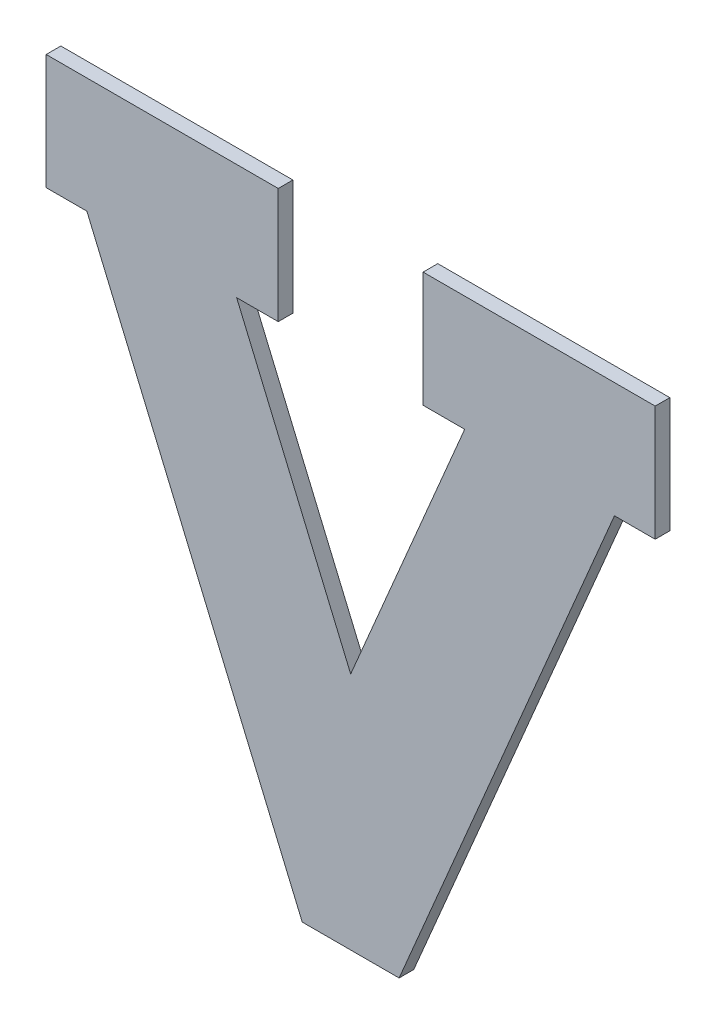
SolidWorks part; units mm, degrees
material "Copper"
ref_plane "Front Plane" through (0, 0, 0) normal (0, 0, 1) x (1, 0, 0)
ref_plane "Top Plane" through (0, 0, 0) normal (0, 1, 0) x (1, 0, 0)
ref_plane "Right Plane" through (0, 0, 0) normal (1, 0, 0) x (0, 0, -1)
sketch "Sketch1" plane through (0, 0, 0) normal (0, 0, 1) x (1, 0, 0)
  line B0 (326.5754, 440.106) -> (356.1251, 440.106)
  line B1 (356.1251, 440.106) -> (276.5171, 252.3248)
  line B2 (276.5171, 252.3248) -> (196.9092, 440.106)
  line B3 (196.9092, 440.106) -> (226.4589, 440.106)
  line B4 (226.4589, 440.106) -> (226.4589, 565.4544)
  line B5 (226.4589, 565.4544) -> (0, 565.4544)
  line B6 (0, 565.4544) -> (0, 440.106)
  line B7 (0, 440.106) -> (39.5592, 440.106)
  line B8 (39.5592, 440.106) -> (226.1378, 0)
  line B9 (226.1378, 0) -> (326.8965, 0)
  line B10 (326.8965, 0) -> (513.4751, 440.106)
  line B11 (513.4751, 440.106) -> (553.0343, 440.106)
  line B12 (553.0343, 440.106) -> (553.0343, 565.4544)
  line B13 (553.0343, 565.4544) -> (326.5754, 565.4544)
  line B14 (326.5754, 565.4544) -> (326.5754, 440.106)
  line B15 (318.4864, 12.7) -> (234.5479, 12.7)
  line B16 (505.065, 452.806) -> (318.4864, 12.7)
  line B17 (540.3343, 452.806) -> (505.065, 452.806)
  line B18 (540.3343, 552.7544) -> (540.3343, 452.806)
  line B19 (339.2754, 552.7544) -> (540.3343, 552.7544)
  line B20 (339.2754, 452.806) -> (339.2754, 552.7544)
  line B21 (375.3033, 452.806) -> (339.2754, 452.806)
  line B22 (276.5171, 219.7869) -> (375.3033, 452.806)
  line B23 (177.731, 452.806) -> (276.5171, 219.7869)
  line B24 (213.7589, 452.806) -> (177.731, 452.806)
  line B25 (213.7589, 552.7544) -> (213.7589, 452.806)
  line B26 (12.7, 552.7544) -> (213.7589, 552.7544)
  line B27 (12.7, 452.806) -> (12.7, 552.7544)
  line B28 (47.9692, 452.806) -> (12.7, 452.806)
  line B29 (234.5479, 12.7) -> (47.9692, 452.806)
sketch_block_instance "V_Block-1"
sketch_block "V_Block"
extrude "Boss-Extrude1" add sketch "Sketch1" along normal blind 12.7 contours B29 B15 B16 B17 B18 B19 B20 B21 B22 B23 B24 B25 B26 B27 B28
